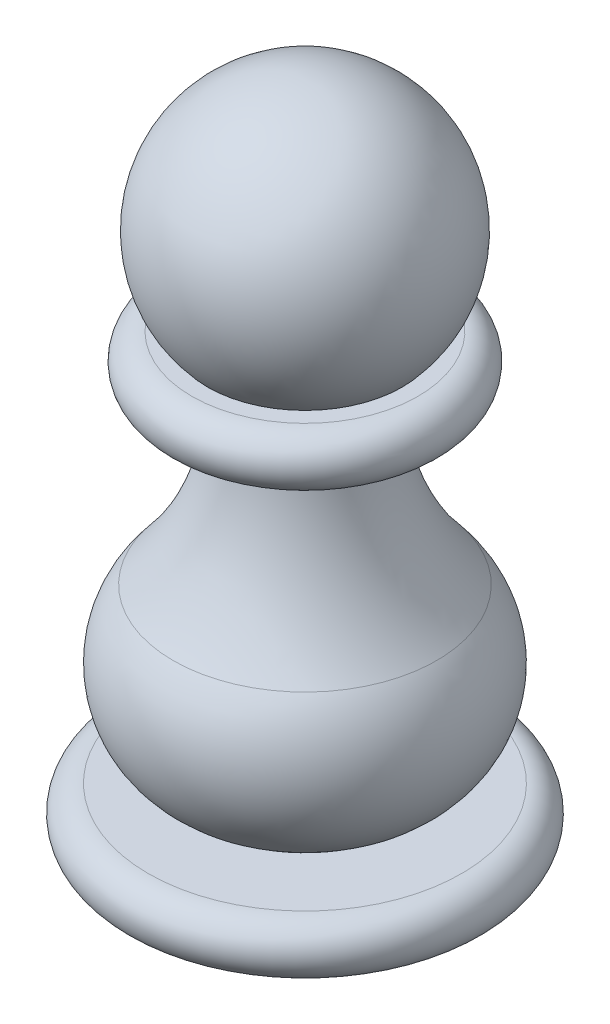
SolidWorks part; units mm, degrees
ref_plane "Front Plane" through (0, 0, 0) normal (0, 0, 1) x (1, 0, 0)
ref_plane "Top Plane" through (0, 0, 0) normal (0, 1, 0) x (1, 0, 0)
ref_plane "Right Plane" through (0, 0, 0) normal (1, 0, 0) x (0, 0, -1)
sketch "Sketch1" plane through (0, 0, 0) normal (0, 0, 1) x (1, 0, 0)
  line L0 (0, 0) -> (0, -16578.2561) construction
  line L1 (0, 0) -> (18, 0)
  line L2 (18, 5.9981) -> (6, 5.9981)
  line L3 (8, 45) -> (13, 45)
  line L4 (13, 51) -> (11.1803, 51)
  line L5 (0, 0) -> (0, 76)
  arc A0 (18, 0) -> (18, 5.9981) centre (18, 2.999) ccw
  arc A1 (6, 5.9981) -> (15.1427, 25.7706) centre (6, 17.9981) ccw
  arc A2 (15.1427, 25.7706) -> (8, 45) centre (37.9993, 45.2018) cw
  arc A3 (13, 45) -> (13, 51) centre (13, 48) ccw
  arc A4 (11.1803, 51) -> (0, 76) centre (0, 61) ccw
  dimension "D2" = 2.999
  dimension "D3" = 25
  dimension "D4" = 3
  dimension "D5" = 30
  dimension "D6" = 12
  dimension "D10" = 15
  dimension "D1" = 18
  dimension "D7" = 18
  dimension "D8" = 13
  dimension "D9" = 8
  dimension "D11" = 76
revolve "Revolve1" add sketch "Sketch1" angle 360 about L0
